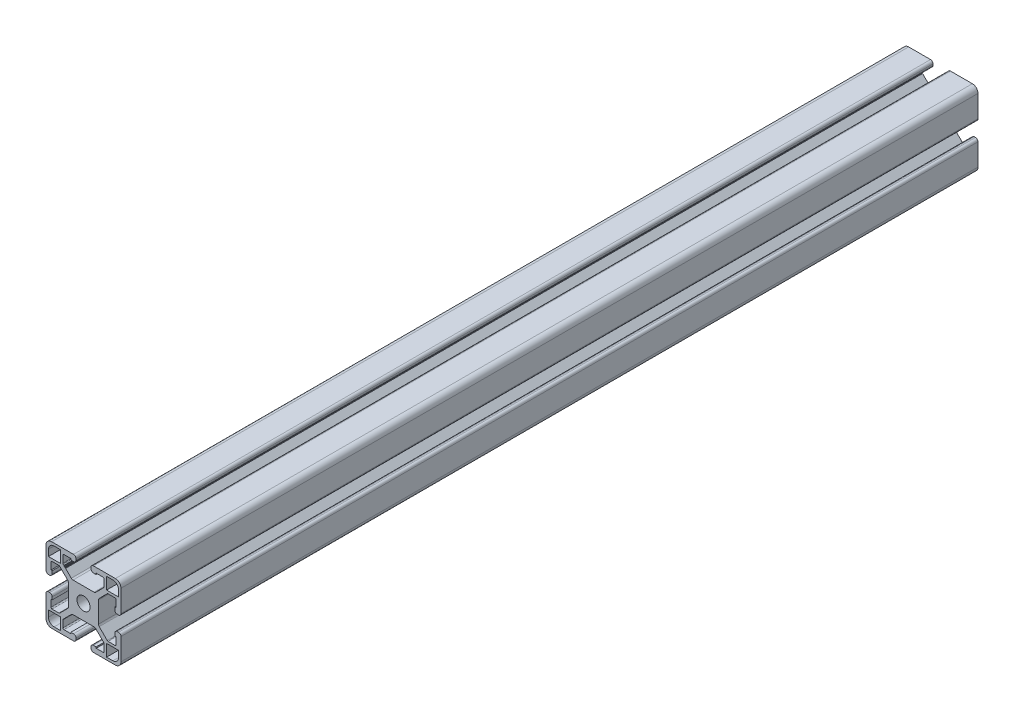
SolidWorks part; units mm, degrees
ref_plane "Front Plane" through (0, 0, 0) normal (0, 0, 1) x (1, 0, 0)
ref_plane "Top Plane" through (0, 0, 0) normal (0, 1, 0) x (1, 0, 0)
ref_plane "Right Plane" through (0, 0, 0) normal (1, 0, 0) x (0, 0, -1)
sketch "Sketch2" plane through (0, 0, 0) normal (0, 0, 1) x (1, 0, 0)
  line L0 (0, 20) -> (0, -20) construction
  line L1 (-20, 0) -> (20, 0) construction
  line L2 (4, -20) -> (20, -20)
  line L3 (20, -20) -> (20, -4)
  line L5 (6.75, -17.36) -> (10.4, -17.36)
  line L7 (0, 0) -> (20, -20) construction
  line L9 (17.36, -6.75) -> (17.36, -10.4)
  line L11 (10.4334, -8.5666) -> (8.5666, -10.4334) construction
  line L12 (11, -16.76) -> (11, -12.8668)
  line L13 (6.1332, -8) -> (11, -12.8668)
  line L14 (16.76, -11) -> (12.8668, -11)
  line L15 (8, -6.1332) -> (12.8668, -11)
  line L16 (4, -20) -> (4, -16.7)
  line L18 (4, -16.7) -> (6.75, -16.7)
  line L19 (6.75, -16.7) -> (6.75, -17.36)
  line L20 (20, -4) -> (16.7, -4)
  line L21 (16.7, -4) -> (16.7, -6.75)
  line L22 (16.7, -6.75) -> (17.36, -6.75)
  line L23 (6.75, -17.36) -> (6.75, -20) construction
  circle A0 centre (0, 0) radius 3.5
  arc A1 (10.4, -17.36) -> (11, -16.76) centre (10.4, -16.76) ccw
  arc A2 (17.36, -10.4) -> (16.76, -11) centre (16.76, -10.4) cw
  point P8 (0, -8)
  point P16 (9.5, -9.5)
  dimension "Center Hole Diameter" = 7
  dimension "D3" = 0.6
  dimension "Rail Height" = 40
  dimension "Rail Width" = 40
  dimension "T-Slot Width" = 8
  dimension "Slot Depth" = 12
  dimension "Inner Slot Width" = 22
  dimension "D1" = 2.75
  dimension "D2" = 3.3
  dimension "D4" = 0.66
sketch "Sketch3" plane through (0, 0, 0) normal (1, 0, 0) x (0, 0, -1)
  line L0 (-228.6, -20) -> (228.6, -20) construction
  line L1 (-203.2, 0) -> (203.2, 0) construction
  dimension "Length" = 457.2
  dimension "D1" = 25.4
sketch "Sketch4" plane through (0, 0, 0) normal (0, 0, 1) x (1, 0, 0)
  line L1 (20, -17) -> (20, -5.32)
  line L2 (20, -4) -> (16.7, -4) construction
  line L3 (16.7, -4) -> (16.7, -6.75) construction
  line L7 (18.02, -4) -> (18.68, -4)
  line L9 (16.7, -5.32) -> (16.7, -6.75)
  line L10 (16.7, -6.75) -> (17.36, -6.75)
  line L11 (17.36, -6.75) -> (17.36, -10.4)
  line L13 (16.76, -11) -> (13.1153, -11)
  line L18 (16.76, -11) -> (12.8668, -11) construction
  line L20 (8, -6.1332) -> (12.8668, -11) construction
  line L22 (4, -20) -> (20, -20) construction
  line L23 (20, -20) -> (20, -4) construction
  line L24 (17, -20) -> (5.32, -20)
  line L25 (4, -18.02) -> (4, -18.68)
  line L26 (4, -20) -> (4, -16.7) construction
  line L27 (4, -16.7) -> (6.75, -16.7) construction
  line L28 (5.32, -16.7) -> (6.75, -16.7)
  line L29 (6.75, -16.7) -> (6.75, -17.36)
  line L30 (6.75, -17.36) -> (10.4, -17.36)
  line L31 (6.1332, -8) -> (11, -12.8668) construction
  line L32 (11, -16.76) -> (11, -12.8668) construction
  line L33 (11, -13.1153) -> (11, -16.76)
  line L34 (0, -8) -> (5.5865, -8)
  line L35 (6.5199, -8.3866) -> (10.8243, -12.691)
  line L36 (12.691, -10.8243) -> (8.3866, -6.5199)
  line L37 (8, 0) -> (8, -5.5865)
  line L38 (-20, 0) -> (20, 0) construction
  line L39 (15.68, -18.68) -> (12.32, -18.68)
  line L40 (12.32, -18.68) -> (12.32, -12.32)
  line L41 (18.68, -12.32) -> (18.68, -15.68)
  line L42 (12.32, -12.32) -> (18.68, -12.32)
  line L43 (0, 0) -> (20, -20) construction
  line L44 (12.32, -18.68) -> (12.32, -20) construction
  line L45 (11, -14.9376) -> (12.32, -14.9376) construction
  line L46 (0, -8) -> (0, -3.5)
  line L47 (8, 0) -> (3.5, 0)
  arc A1 (18.68, -4) -> (20, -5.32) centre (18.68, -5.32) cw
  arc A10 (16.7, -5.32) -> (18.02, -4) centre (18.02, -5.32) cw
  arc A12 (17, -20) -> (20, -17) centre (17, -17) ccw
  arc A13 (4, -18.02) -> (5.32, -16.7) centre (5.32, -18.02) cw
  arc A14 (4, -18.68) -> (5.32, -20) centre (5.32, -18.68) ccw
  arc A15 (10.4, -17.36) -> (11, -16.76) centre (10.4, -16.76) ccw construction
  arc A16 (10.4, -17.36) -> (11, -16.76) centre (10.4, -16.76) ccw
  arc A17 (10.8243, -12.691) -> (11, -13.1153) centre (10.4, -13.1153) cw
  arc A18 (5.5865, -8) -> (6.5199, -8.3866) centre (5.5865, -9.32) cw
  arc A19 (16.76, -11) -> (17.36, -10.4) centre (16.76, -10.4) ccw construction
  arc A20 (16.76, -11) -> (17.36, -10.4) centre (16.76, -10.4) ccw
  arc A21 (12.691, -10.8243) -> (13.1153, -11) centre (13.1153, -10.4) ccw
  arc A22 (8, -5.5865) -> (8.3866, -6.5199) centre (9.32, -5.5865) ccw
  arc A23 (18.68, -15.68) -> (15.68, -18.68) centre (15.68, -15.68) cw
  circle A24 centre (0, 0) radius 3.5 construction
  arc A25 (0, -3.5) -> (3.5, 0) centre (0, 0) ccw
  point P74 (4, -18.35)
  dimension "D2" = 1.32
  dimension "D1" = 1.32
  dimension "D3" = 3
  dimension "D4" = 3
extrude "Boss-Extrude1" add sketch "Sketch4" along normal mid plane 457.2
mirror "Mirror1" about plane through (0, 0, 0) normal (1, 0, 0) of bodies 134
mirror "Mirror2" about plane through (0, 0, 0) normal (0, 1, 0) of bodies 135
sketch "Sketch5" plane through (0, 0, 0) normal (0, 0, 1) x (1, 0, 0)
  line L1 (-10.4532, 12.32) -> (-10.4532, 11.99)
  line L2 (-6.5199, 8.3866) -> (-10.8243, 12.691) construction
  line L3 (-10.4532, 11.99) -> (-10.1232, 11.99)
  line L4 (-10.1232, 11.99) -> (-9.8899, 11.7567)
  line L5 (-9.8899, 11.7567) -> (-9.8899, 11.4267)
  line L6 (-9.8899, 11.4267) -> (-9.5599, 11.4267)
  line L7 (-10.4532, 12.32) -> (-9.5599, 12.32)
  line L8 (-9.5599, 12.32) -> (-9.5599, 11.4267)
  dimension "D1" = 0.33
extrude "Cut-Extrude1" cut sketch "Sketch5" against normal through all both and the other way through all
equation "\"D3@Sketch2\"=\"T-Slot Width@Sketch2\"*0.075"
equation "\"D1@Boss-Extrude1\"=\"Length@Sketch3\""
equation "\"D1@Sketch2\"=\"Inner Slot Width@Sketch2\"*0.125"
equation "\"D2@Sketch2\"=\"Slot Depth@Sketch2\"*0.275"
equation "\"D4@Sketch2\"=\"D2@Sketch2\"*0.2"
equation "\"D1@Sketch4\"=\"D2@Sketch2\"*0.4"
equation "\"D2@Sketch4\"=\"D1@Sketch4\""
equation "\"D3@Sketch4\"=\"Rail Height@Sketch2\"*0.075"
equation "\"D4@Sketch4\"=\"Rail Height@Sketch2\"*0.075"
equation "\"D1@Sketch5\"=\"D4@Sketch2\"*0.5"
